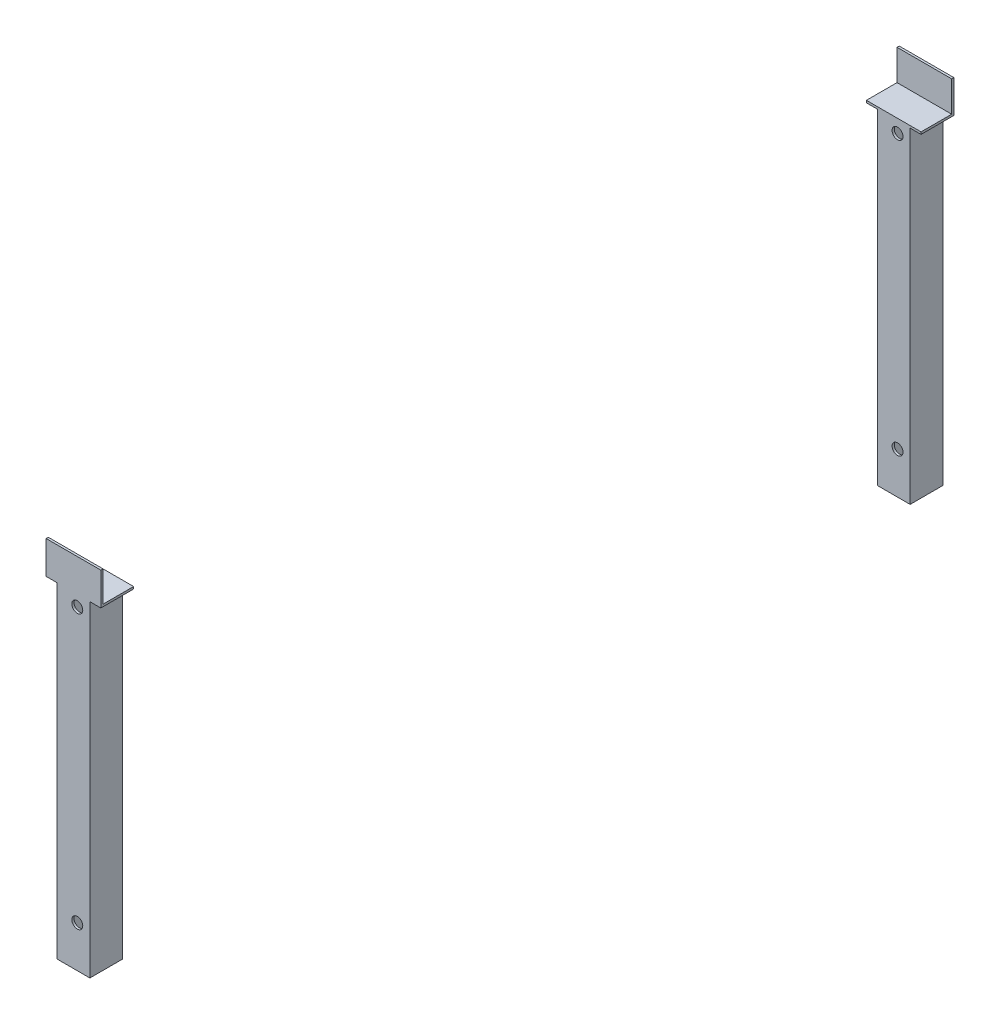
SolidWorks part; units mm, degrees
other "Markup1"
sketch "Sketch4" plane through (25, 480, -15) normal (0.4319, 0.526, -0.7326) x (-0.6581, -0.3717, -0.6548)
ref_plane "Front Plane" through (0, 0, 0) normal (0, 0, 1) x (1, 0, 0)
ref_plane "Top Plane" through (0, 0, 0) normal (0, 1, 0) x (1, 0, 0)
ref_plane "Right Plane" through (0, 0, 0) normal (1, 0, 0) x (0, 0, -1)
sketch "Sketch1" plane through (0, 0, 0) normal (0, 1, 0) x (1, 0, 0)
  line L1 (-15, 15) -> (15, 15)
  line L2 (-15, 15) -> (-15, -15)
  line L3 (-15, -15) -> (15, -15)
  line L4 (15, 15) -> (15, -15)
  line L5 (-15, 15) -> (15, -15) construction
  line L6 (-15, -15) -> (15, 15) construction
  point P0 (0, 0)
  dimension "D1" = 30
  dimension "D2" = 30
extrude "Boss-Extrude1" add sketch "Sketch1" along normal blind 298
shell "Shell1" thickness 2
sketch "Sketch2" plane through (0, 0, 15) normal (0, 0, 1) x (1, 0, 0)
  line L0 (-15, 298) -> (-25, 298)
  line L1 (-25, 298) -> (-25, 328)
  line L2 (-25, 328) -> (25, 328)
  line L3 (25, 328) -> (25, 298)
  line L4 (25, 298) -> (15, 298)
  line L5 (-15, 298) -> (15, 298)
  dimension "D1" = 10
  dimension "D2" = 30
extrude "Boss-Extrude2" add sketch "Sketch2" against normal blind 2
sketch "Sketch3" plane through (0, 298, 0) normal (0, 1, 0) x (1, 0, 0)
  line L0 (-15, -13) -> (-25, -13)
  line L1 (-25, -13) -> (-25, 15)
  line L2 (25, -13) -> (25, 15)
  line L3 (25, 15) -> (-25, 15)
  line L4 (-15, -13) -> (25, -13)
extrude "Boss-Extrude4" add sketch "Sketch3" along normal blind 2
sketch "Sketch5" plane through (0, 0, 15) normal (0, 0, 1) x (1, 0, 0)
  line L0 (0, 328) -> (0, 288) construction
  line L1 (25, 328) -> (-25, 328) construction
  line L2 (0, 288) -> (3.5, 288) construction
  line L3 (3.5, 288) -> (3.5, 38) construction
  circle A0 centre (3.5, 288) radius 5
  circle A1 centre (3.5, 38) radius 5
  dimension "D3" = 10
  dimension "D5" = 10
  dimension "D1" = 40
  dimension "D2" = 3.5
  dimension "D4" = 250
extrude "Cut-Extrude1" cut sketch "Sketch5" against normal through all
ref_plane "Plane1" through (0, 0, -375) normal (0, 0, 1) x (1, 0, 0)
mirror "Mirror2" about plane through (0, 0, -375) normal (0, 0, 1) of bodies 104
